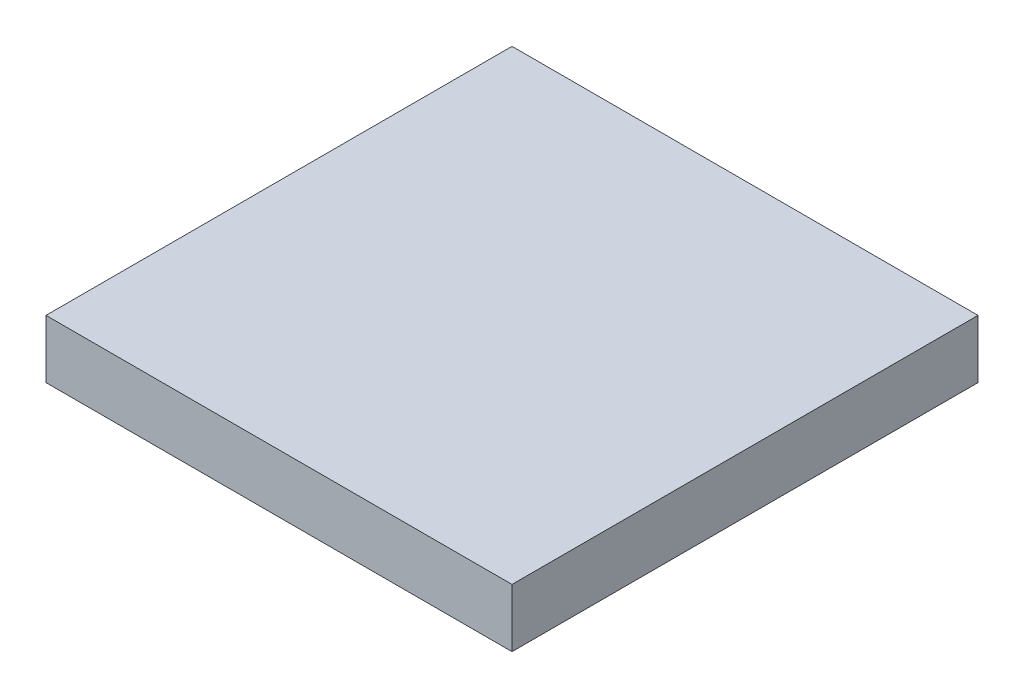
SolidWorks part; units mm, degrees
ref_plane "Front Plane" through (0, 0, 0) normal (0, 0, 1) x (1, 0, 0)
ref_plane "Top Plane" through (0, 0, 0) normal (0, 1, 0) x (1, 0, 0)
ref_plane "Right Plane" through (0, 0, 0) normal (1, 0, 0) x (0, 0, -1)
sketch "Sketch1" plane through (0, 0, 0) normal (0, 1, 0) x (1, 0, 0)
  line L1 (0, 0) -> (25.4, 0)
  line L2 (0, 0) -> (0, 25.4)
  line L3 (0, 25.4) -> (25.4, 25.4)
  line L4 (25.4, 0) -> (25.4, 25.4)
  dimension "D1" = 25.4
  dimension "D2" = 25.4
extrude "Boss-Extrude1" add sketch "Sketch1" along normal blind 3.175
